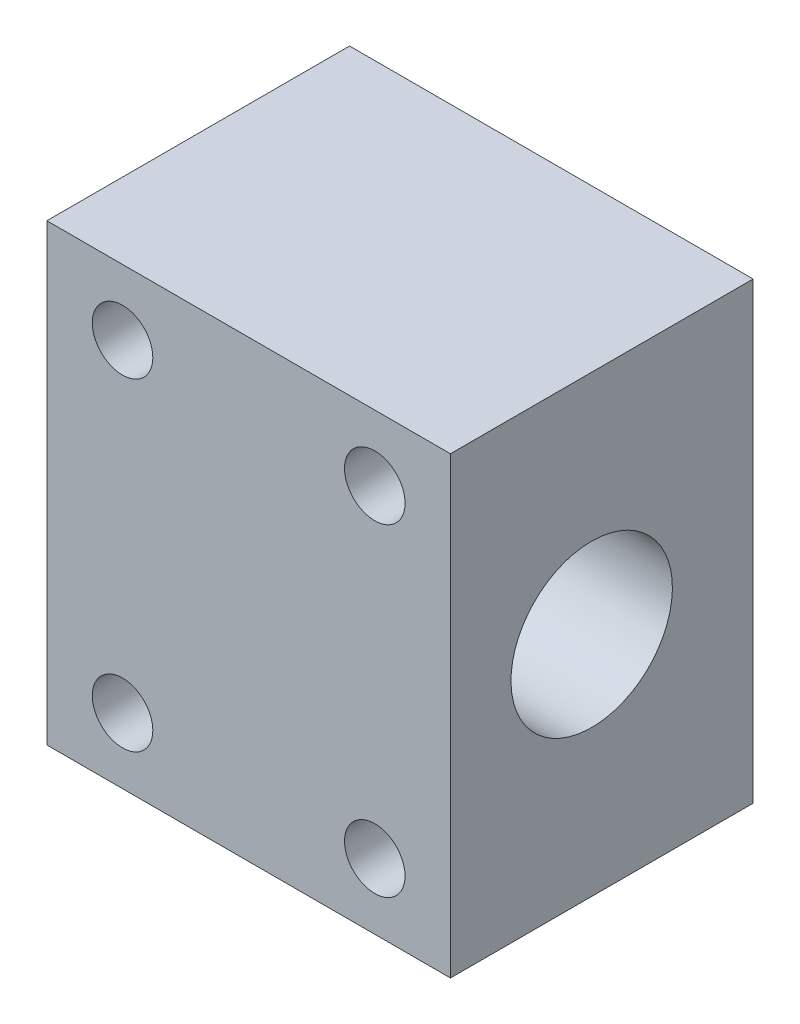
SolidWorks part; units mm, degrees
material "3.3535 (EN-AW 5754)"
ref_plane "Front Plane" through (0, 0, 0) normal (0, 0, 1) x (1, 0, 0)
ref_plane "Top Plane" through (0, 0, 0) normal (0, 1, 0) x (1, 0, 0)
ref_plane "Right Plane" through (0, 0, 0) normal (1, 0, 0) x (0, 0, -1)
sketch "Sketch1" plane through (0, 0, 0) normal (0, 0, 1) x (1, 0, 0)
  line L1 (-20, 22.5) -> (20, 22.5)
  line L2 (-20, 22.5) -> (-20, -22.5)
  line L3 (-20, -22.5) -> (20, -22.5)
  line L4 (20, 22.5) -> (20, -22.5)
  line L5 (-20, 22.5) -> (20, -22.5) construction
  line L6 (-20, -22.5) -> (20, 22.5) construction
  point P0 (0, 0)
  dimension "D1" = 40
  dimension "D2" = 45
extrude "Boss-Extrude1" add sketch "Sketch1" along normal blind 30
sketch "Sketch2" plane through (20, 0, 0) normal (1, 0, 0) x (0, 0, -1)
  line L3 (-16, 0) -> (0, 0) construction
  line L4 (0, -22.5) -> (0, 22.5) construction
  circle A0 centre (-16, 0) radius 8
  dimension "D2" = 16
  dimension "D1" = 16
extrude "Cut-Extrude1" cut sketch "Sketch2" against normal through all
sketch "Sketch3" plane through (0, 0, 30) normal (0, 0, 1) x (1, 0, 0)
  line L0 (-20, 22.5) -> (-20, -22.5) construction
  line L5 (12.5, -16) -> (-12.5, 16) construction
  line L6 (12.5, 16) -> (-12.5, -16) construction
  line L7 (20, 22.5) -> (-20, 22.5) construction
  circle A0 centre (-12.5, 16) radius 3
  circle A1 centre (12.5, 16) radius 3
  circle A2 centre (12.5, -16) radius 3
  circle A3 centre (-12.5, -16) radius 3
  point P0 (0, 0)
  dimension "D3" = 6
  dimension "D1" = 32
  dimension "D2" = 25
  dimension "D4" = 2
  dimension "D5" = 2
extrude "Cut-Extrude2" cut sketch "Sketch3" against normal through all
